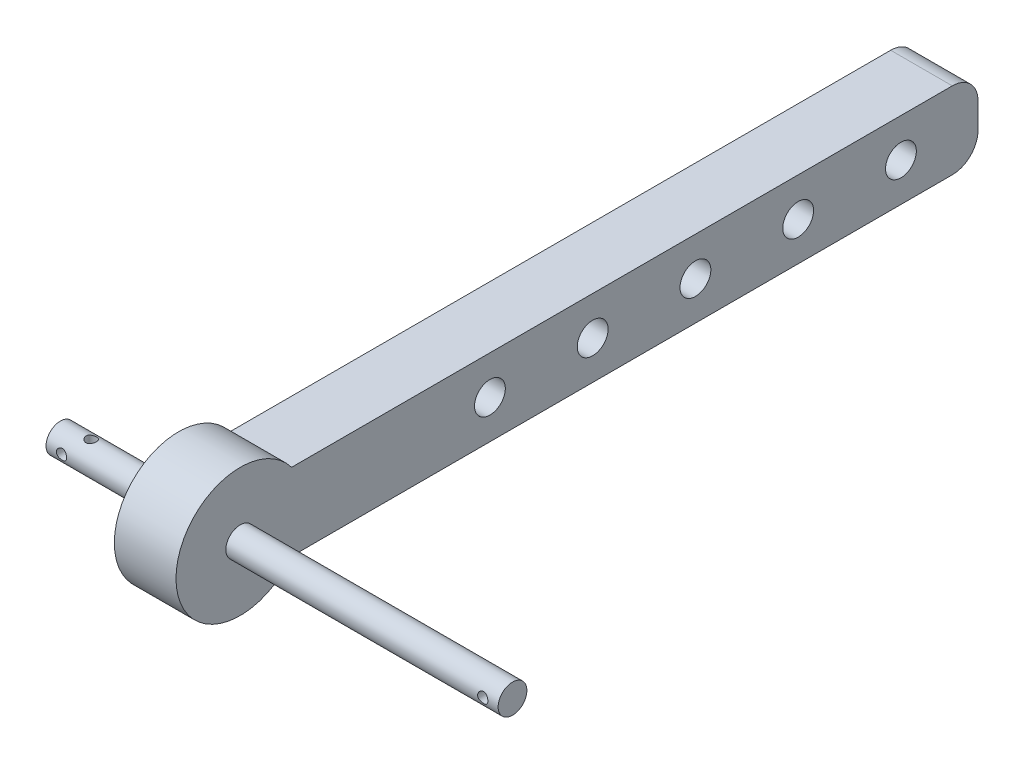
SolidWorks part; units mm, degrees
ref_plane "前视基准面" through (0, 0, 0) normal (0, 0, 1) x (1, 0, 0)
ref_plane "上视基准面" through (0, 0, 0) normal (0, 1, 0) x (1, 0, 0)
ref_plane "右视基准面" through (0, 0, 0) normal (1, 0, 0) x (0, 0, -1)
other "Configuration Table"
sketch "草图1" plane through (0, 0, 0) normal (1, 0, 0) x (0, 0, -1)
  line L1 (0, 0) -> (150, 0)
  line L2 (0, 0) -> (0, 15)
  line L3 (0, 15) -> (150, 15)
  line L4 (150, 0) -> (150, 15)
  dimension "D1" = 15
  dimension "D2" = 150
extrude "凸台-拉伸1" add sketch "草图1" along normal blind 12
fillet "圆角1" radius 5 4 edges at (6, 0, -150) (6, 15, -150) (6, 0, 0) (6, 15, 0)
sketch "草图6" plane through (12, 0, 0) normal (1, 0, 0) x (0, 0, -1)
  circle A0 centre (6.4, 7.5) radius 12.5
extrude "凸台-拉伸2" add sketch "草图6" against normal up to surface (12 mm away) up to face at (0, 7.5, -75)
sketch "草图15" plane through (0, 0, 0) normal (-1, 0, 0) x (0, 0, 1)
  circle A2 centre (-6.4, 7.5) radius 2.8
  dimension "D1" = 5.6
extrude "凸台-拉伸5" add sketch "草图15" along normal blind 23 and the other way blind 65
sketch "草图16" plane through (0, 0, 0) normal (0, 0, 1) x (1, 0, 0)
  line L0 (-23, 7.5) -> (-24.7951, 7.5) construction
  line L1 (-23, 10.3) -> (-23, 4.7) construction
  line L2 (65, 7.5) -> (28.4852, 7.5) construction
  line L3 (65, 4.7) -> (65, 10.3) construction
  circle A0 centre (-20, 7.5) radius 1
  circle A1 centre (62, 7.5) radius 1
  dimension "D2" = 2
  dimension "D3" = 2
  dimension "D1" = 3
  dimension "D4" = 3
extrude "切除-拉伸9" cut sketch "草图16" against normal up to next
sketch "草图17" plane through (0, 0, 0) normal (-1, 0, 0) x (0, 0, 1)
  line L0 (-150, 7.5) -> (-31.7081, 7.5) construction
  line L1 (-150, 5) -> (-150, 10) construction
  circle A0 centre (-135, 7.5) radius 3
  circle A1 centre (-115, 7.5) radius 3
  circle A2 centre (-95, 7.5) radius 3
  circle A3 centre (-75, 7.5) radius 3
  circle A4 centre (-55, 7.5) radius 3
  dimension "D6" = 6
  dimension "D7" = 6
  dimension "D8" = 6
  dimension "D9" = 6
  dimension "D10" = 6
  dimension "D1" = 15
  dimension "D2" = 20
  dimension "D3" = 20
  dimension "D4" = 20
  dimension "D5" = 20
extrude "切除-拉伸10" cut sketch "草图17" against normal up to next
sketch "草图18" plane through (0, 0, 0) normal (0, 1, 0) x (1, 0, 0)
  line L0 (-23, 6.4) -> (-12.4483, 6.4) construction
  line L1 (-23, 9.2) -> (-23, 3.6) construction
  circle A0 centre (-17, 6.4) radius 1
  dimension "D2" = 2
  dimension "D1" = 6
extrude "切除-拉伸11" cut sketch "草图18" along normal blind 15
